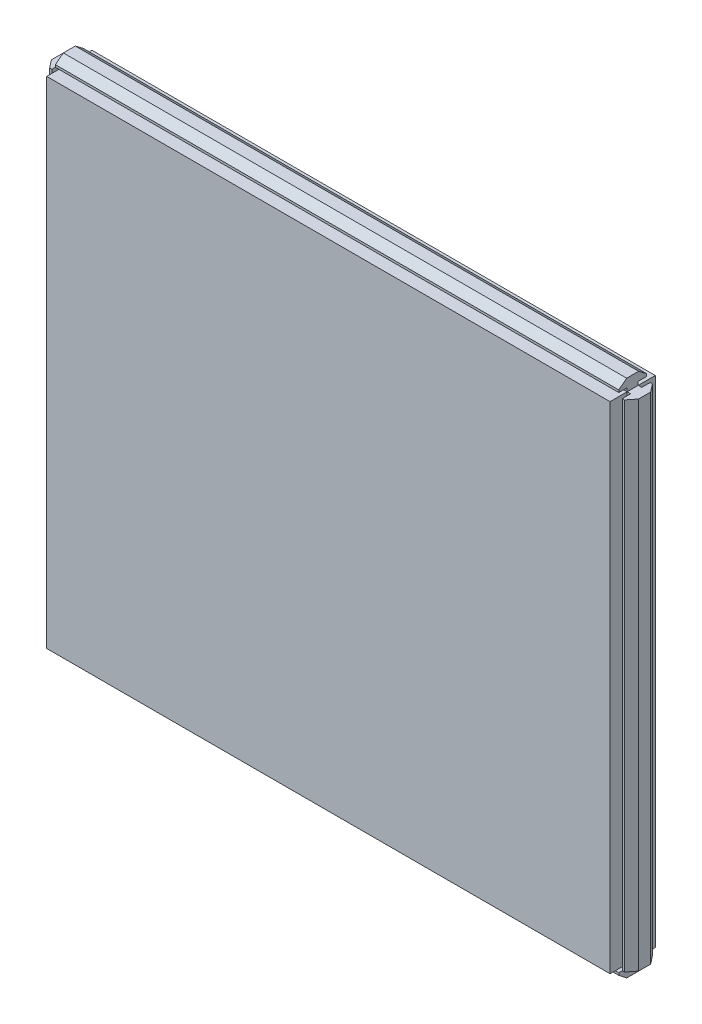
SolidWorks part; units mm, degrees
ref_plane "Plan de face" through (0, 0, 0) normal (0, 0, 1) x (1, 0, 0)
ref_plane "Plan de dessus" through (0, 0, 0) normal (0, 1, 0) x (1, 0, 0)
ref_plane "Plan de droite" through (0, 0, 0) normal (1, 0, 0) x (0, 0, -1)
sketch "Esquisse1" plane through (0, 0, 0) normal (0, 0, 1) x (1, 0, 0)
  line L0 (-33.9101, 30.6713) -> (215.0899, 30.6713)
  line L1 (215.0899, 30.6713) -> (215.0899, 25.3713)
  line L2 (215.0899, 25.3713) -> (220.3899, 25.3713)
  line L3 (220.3899, 25.3713) -> (220.3899, -193.6287)
  line L4 (220.3899, -193.6287) -> (215.0899, -193.6287)
  line L5 (215.0899, -193.6287) -> (215.0899, -198.9287)
  line L6 (215.0899, -198.9287) -> (-33.9101, -198.9287)
  line L7 (-33.9101, -198.9287) -> (-33.9101, -193.6287)
  line L8 (-33.9101, -193.6287) -> (-39.2101, -193.6287)
  line L9 (-39.2101, -193.6287) -> (-39.2101, 25.3713)
  line L10 (-39.2101, 25.3713) -> (-33.9101, 25.3713)
  line L11 (-33.9101, 25.3713) -> (-33.9101, 30.6713)
  dimension "D1" = 249
  dimension "D2" = 5.3
  dimension "D3" = 5.3
  dimension "D4" = 219
  dimension "D5" = 5.3
  dimension "D6" = 5.3
  dimension "D7" = 249
  dimension "D8" = 5.3
  dimension "D9" = 5.3
  dimension "D10" = 219
  dimension "D11" = 5.3
  dimension "D12" = 5.3
extrude "Boss.-Extru.1" add sketch "Esquisse1" along normal blind 20
sketch "Esquisse2" plane through (215.0899, 0, 0) normal (1, 0, 0) x (0, 0, -1)
  line L0 (-20, 25.3713) -> (-12.45, 25.3713)
  line L1 (-20, 25.3713) -> (0, 25.3713) construction
  line L2 (-12.45, 25.3713) -> (-12.45, 26.9213)
  line L3 (-12.45, 26.9213) -> (-16.15, 26.9213)
  line L4 (-16.15, 26.9213) -> (-16.15, 27.9213)
  line L5 (-16.15, 27.9213) -> (-12.65, 30.6713)
  line L6 (-20, 30.6713) -> (0, 30.6713) construction
  dimension "D1" = 7.55
  dimension "D2" = 1.55
  dimension "D3" = 3.7
  dimension "D4" = 1
  dimension "D5" = 7.35
extrude "Enlèv. mat.-Extru.2" cut sketch "Esquisse2" against normal blind 249 and the other way through all
sketch "Esquisse3" plane through (215.0899, 0, 0) normal (1, 0, 0) x (0, 0, -1)
  line L0 (0, 25.3713) -> (-7.55, 25.3713)
  line L1 (-12.45, 25.3713) -> (0, 25.3713) construction
  line L2 (-7.55, 25.3713) -> (-7.55, 26.9213)
  line L3 (-7.55, 26.9213) -> (-3.85, 26.9213)
  line L4 (-3.85, 26.9213) -> (-3.85, 28.0205)
  line L5 (-3.85, 28.0205) -> (-7.35, 30.6713)
  line L6 (-12.65, 30.6713) -> (0, 30.6713) construction
  dimension "D1" = 3.7
  dimension "D2" = 7.55
  dimension "D3" = 1.55
  dimension "D4" = 7.35
extrude "Enlèv. mat.-Extru.3" cut sketch "Esquisse3" against normal blind 249 and the other way through all flip side to cut
sketch "Esquisse5" plane through (0, 25.3713, 0) normal (0, 1, 0) x (1, 0, 0)
  line L0 (215.0899, -7.55) -> (215.0899, 0)
  line L1 (220.3899, 0) -> (-39.2101, 0) construction
  line L2 (215.0899, -7.55) -> (216.6399, -7.55)
  line L3 (216.6399, -7.55) -> (216.6399, -3.85)
  line L4 (216.6399, -3.85) -> (217.6399, -3.85)
  line L5 (217.6399, -3.85) -> (220.3899, -7.35)
  line L6 (220.3899, -20) -> (220.3899, 0) construction
  dimension "D1" = 7.55
  dimension "D2" = 1.55
  dimension "D3" = 3.7
  dimension "D4" = 1
  dimension "D5" = 7.35
extrude "Enlèv. mat.-Extru.4" cut sketch "Esquisse5" against normal blind 219 and the other way through all
sketch "Esquisse7" plane through (0, 25.3713, 0) normal (0, 1, 0) x (1, 0, 0)
  line L0 (215.0899, -12.45) -> (215.0899, -20)
  line L1 (220.3899, -20) -> (-39.2101, -20) construction
  line L2 (215.0899, -12.45) -> (216.6399, -12.45)
  line L3 (216.6399, -12.45) -> (216.6399, -16.15)
  line L4 (216.6399, -16.15) -> (217.6399, -16.15)
  line L5 (217.6399, -16.15) -> (220.3899, -12.65)
  line L6 (220.3899, -20) -> (220.3899, -7.35) construction
  dimension "D1" = 7.55
  dimension "D2" = 1.55
  dimension "D3" = 3.7
  dimension "D4" = 1
  dimension "D5" = 7.35
extrude "Enlèv. mat.-Extru.5" cut sketch "Esquisse7" against normal blind 219 and the other way through all flip side to cut
sketch "Esquisse9" plane through (0, 25.3713, 0) normal (0, 1, 0) x (1, 0, 0)
  line L0 (-33.9101, -12.45) -> (-33.9101, -20)
  line L1 (215.0899, -20) -> (-39.2101, -20) construction
  line L2 (-33.9101, -12.45) -> (-35.4601, -12.45)
  line L3 (-35.4601, -12.45) -> (-35.4601, -16.15)
  line L4 (-35.4601, -16.15) -> (-36.4601, -16.15)
  line L5 (-36.4601, -16.15) -> (-39.2101, -12.65)
  line L6 (-39.2101, -20) -> (-39.2101, 0) construction
  dimension "D1" = 7.55
  dimension "D2" = 1.55
  dimension "D3" = 3.7
  dimension "D4" = 1
  dimension "D5" = 7.35
extrude "Enlèv. mat.-Extru.7" cut sketch "Esquisse9" against normal blind 219 and the other way through all
sketch "Esquisse10" plane through (0, 25.3713, 0) normal (0, 1, 0) x (1, 0, 0)
  line L0 (-33.9101, -7.55) -> (-33.9101, 0)
  line L1 (215.0899, 0) -> (-39.2101, 0) construction
  line L2 (-33.9101, -7.55) -> (-35.4601, -7.55)
  line L3 (-35.4601, -7.55) -> (-35.4601, -3.85)
  line L4 (-35.4601, -3.85) -> (-36.4601, -3.85)
  line L5 (-36.4601, -3.85) -> (-39.2101, -7.35)
  line L7 (-39.2101, -12.65) -> (-39.2101, 0) construction
  dimension "D1" = 7.55
  dimension "D2" = 1.55
  dimension "D3" = 3.7
  dimension "D4" = 1
  dimension "D5" = 7.35
extrude "Enlèv. mat.-Extru.8" cut sketch "Esquisse10" against normal blind 219 and the other way through all flip side to cut
sketch "Esquisse12" plane through (-33.9101, 0, 0) normal (-1, 0, 0) x (0, 0, 1)
  line L0 (12.45, -193.6287) -> (20, -193.6287)
  line L1 (20, 25.3713) -> (20, -198.9287) construction
  line L2 (12.45, -193.6287) -> (12.45, -195.1787)
  line L3 (12.45, -195.1787) -> (16.15, -195.1787)
  line L4 (16.15, -195.1787) -> (16.15, -196.1787)
  line L5 (16.15, -196.1787) -> (12.65, -198.9287)
  line L6 (20, -198.9287) -> (0, -198.9287) construction
  dimension "D1" = 7.55
  dimension "D2" = 1.55
  dimension "D3" = 3.7
  dimension "D4" = 1
  dimension "D5" = 7.35
extrude "Enlèv. mat.-Extru.9" cut sketch "Esquisse12" against normal blind 249 and the other way through all
sketch "Esquisse13" plane through (-33.9101, 0, 0) normal (-1, 0, 0) x (0, 0, 1)
  line L0 (7.55, -193.6287) -> (0, -193.6287)
  line L1 (0, 25.3713) -> (0, -198.9287) construction
  line L2 (7.55, -193.6287) -> (7.55, -195.1787)
  line L3 (7.55, -195.1787) -> (3.85, -195.1787)
  line L4 (3.85, -195.1787) -> (3.85, -196.1787)
  line L5 (3.85, -196.1787) -> (7.35, -198.9287)
  line L6 (12.65, -198.9287) -> (0, -198.9287) construction
  dimension "D1" = 7.55
  dimension "D2" = 1.55
  dimension "D3" = 3.7
  dimension "D4" = 1
  dimension "D5" = 7.35
extrude "Enlèv. mat.-Extru.10" cut sketch "Esquisse13" against normal blind 249 and the other way through all flip side to cut
